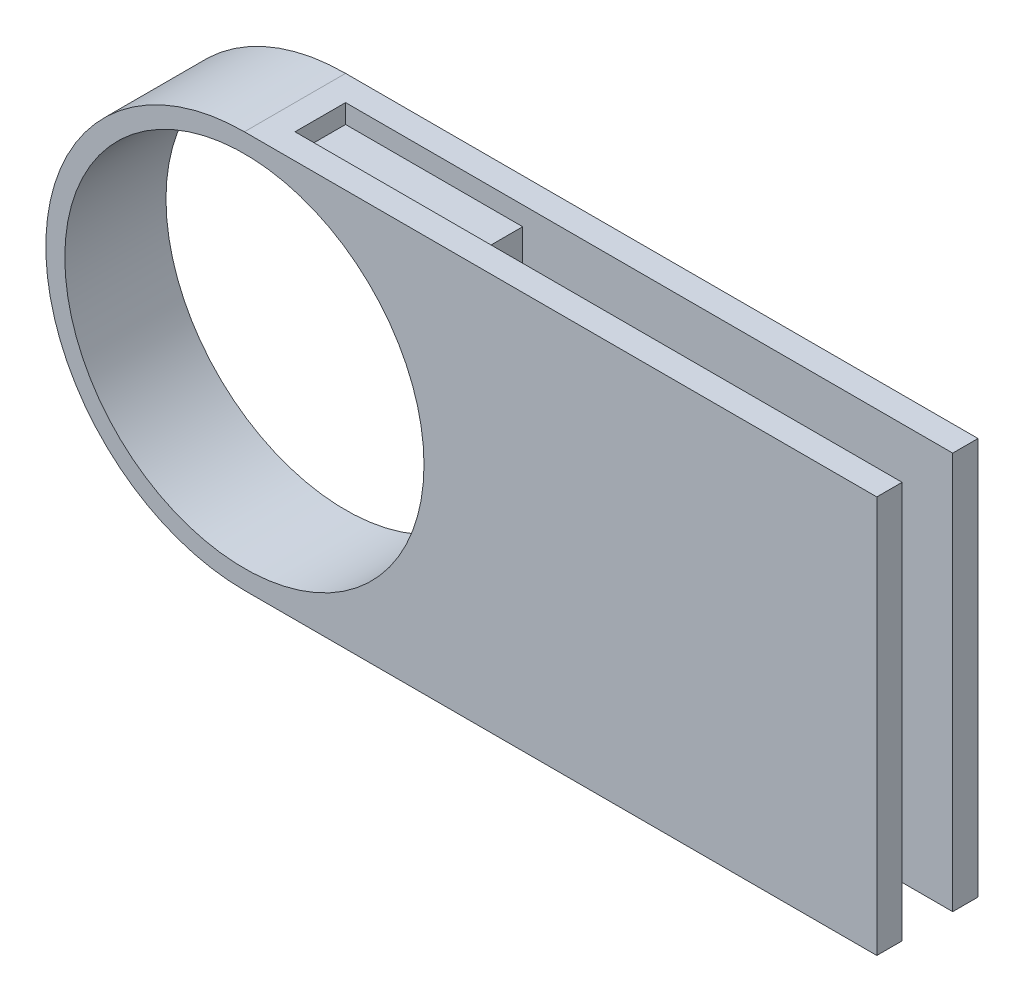
SolidWorks part; units mm, degrees
ref_plane "Front Plane" through (0, 0, 0) normal (0, 0, 1) x (1, 0, 0)
ref_plane "Top Plane" through (0, 0, 0) normal (0, 1, 0) x (1, 0, 0)
ref_plane "Right Plane" through (0, 0, 0) normal (1, 0, 0) x (0, 0, -1)
sketch "Sketch1" plane through (0, 0, 0) normal (0, 0, 1) x (1, 0, 0)
  circle A0 centre (0, 0) radius 19.939
  dimension "D1" = 39.878
extrude "circle extrude" add sketch "Sketch1" along normal blind 7.62
sketch "Sketch3" plane through (0, 0, 0) normal (1, 0, 0) x (0, 0, -1)
  line L0 (0, 55) -> (0, -55) construction
  line L1 (-7.62, 19.939) -> (0, 19.939)
  line L2 (-7.62, 19.939) -> (-7.62, -19.939)
  line L3 (-7.62, -19.939) -> (0, -19.939)
  line L4 (0, 19.939) -> (0, -19.939)
  line L5 (-7.62, -19.939) -> (0, -19.939) construction
extrude "rectangle extrude" add sketch "Sketch3" along normal blind 63.5
sketch "Sketch2" plane through (0, 0, 7.62) normal (0, 0, 1) x (1, 0, 0)
  circle A0 centre (0, 0) radius 18.034
  dimension "D1" = 36.068
extrude "cricle cut" cut sketch "Sketch2" against normal through all
sketch "Sketch4" plane through (0, 0, 7.62) normal (0, 0, 1) x (1, 0, 0)
  line L0 (63.5, 19.939) -> (63.5, -19.939) construction
  line L1 (0, 18.034) -> (61.595, 18.034)
  line L2 (0, 18.034) -> (0, -18.034)
  line L3 (0, -18.034) -> (61.595, -18.034)
  line L4 (61.595, 18.034) -> (61.595, -18.034)
  line L5 (63.5, -19.939) -> (0, -19.939) construction
  circle A0 centre (0, 0) radius 18.034 construction
  dimension "D1" = 1.905
  dimension "D2" = 1.905
extrude "frame cut" [suppressed] cut sketch "Sketch4" against normal through all flip side to cut
sketch "Sketch10" plane through (0, 0, 0) normal (0, 0, -1) x (-1, 0, 0)
  line L2 (0, 19.939) -> (-63.5, 19.939)
  line L18 (0, 19.939) -> (-63.5, 19.939)
  line L21 (-63.5, 19.939) -> (-63.5, -19.939)
  line L23 (-63.5, 19.939) -> (-63.5, -19.939)
  line L24 (-63.5, -19.939) -> (0, -19.939)
  line L25 (-63.5, -19.939) -> (0, -19.939)
  arc A1 (0, -19.939) -> (0, 19.939) centre (0, 0) ccw
  arc A10 (0, -19.939) -> (0, 19.939) centre (0, 0) ccw
  dimension "D1" = 0
extrude "extension" add sketch "Sketch10" along normal blind 2.54
ref_plane "Plane2" through (20.32, 0, 0) normal (1, 0, 0) x (0, 0, -1)
sketch "Sketch15" plane through (0, 0, 0) normal (0, 0, 1) x (1, 0, 0)
  circle A0 centre (0, 0) radius 18.034
  dimension "D1" = 36.068
extrude "circle cut 2" cut sketch "Sketch15" against normal through all
sketch "Sketch16" plane through (20.32, 0, 0) normal (1, 0, 0) x (0, 0, -1)
  line L0 (2.54, 19.939) -> (-7.62, 19.939) construction
  line L1 (0, -19.939) -> (-5.08, -19.939)
  line L2 (0, -19.939) -> (0, 19.939)
  line L3 (0, 19.939) -> (-5.08, 19.939)
  line L4 (-5.08, -19.939) -> (-5.08, 19.939)
  line L5 (0, -19.939) -> (-5.08, 19.939) construction
  line L6 (0, 19.939) -> (-5.08, -19.939) construction
  line L7 (-7.62, -19.939) -> (2.54, -19.939) construction
  point P0 (-2.54, 0)
  dimension "D1" = 2.54
  dimension "D2" = 5.08
extrude "middle cut" cut sketch "Sketch16" along normal through all
sketch "Sketch19" plane through (20.32, 0, 0) normal (1, 0, 0) x (0, 0, -1)
  circle A0 centre (-2.54, 0) radius 1.905
  point P2 (0, 0)
  dimension "D1" = 3.81
  dimension "D2" = 2.54
sketch "Sketch18" plane through (20.32, 0, 0) normal (1, 0, 0) x (0, 0, -1)
  line L0 (0, 19.939) -> (-5.08, 19.939) construction
  line L1 (-5.08, 19.939) -> (0, 19.939)
  line L2 (-5.08, 19.939) -> (-5.08, 18.034)
  line L3 (-5.08, 18.034) -> (0, 18.034)
  line L4 (0, 19.939) -> (0, 18.034)
  point P6 (0, 0)
  point P9 (0, 0)
extrude "Cut-Extrude5" cut sketch "Sketch18" against normal blind 17.78
sketch "Sketch17" plane through (0, 0, 7.62) normal (0, 0, 1) x (1, 0, 0)
  line L0 (0, 19.939) -> (63.5, 19.939)
  line L1 (0, 18.034) -> (63.5, 18.034)
  line L2 (63.5, 19.939) -> (63.5, -19.939) construction
  line L3 (63.5, 18.034) -> (63.5, 19.939)
  line L4 (0, -18.034) -> (63.5, -18.034)
  line L5 (63.5, -18.034) -> (63.5, -19.939)
  line L6 (63.5, -19.939) -> (0, -19.939)
  arc A0 (0, 19.939) -> (0, -19.939) centre (0, 0) ccw
  circle A1 centre (0, 0) radius 18.034 construction
  arc A2 (0, 18.034) -> (0, -18.034) centre (0, 0) ccw
  point P1 (0, 0)
  point P19 (0, 0)
  point P21 (0, 0)
  point P22 (0, 0)
extrude "for spring extrude" add sketch "Sketch19" along normal blind 2.54
